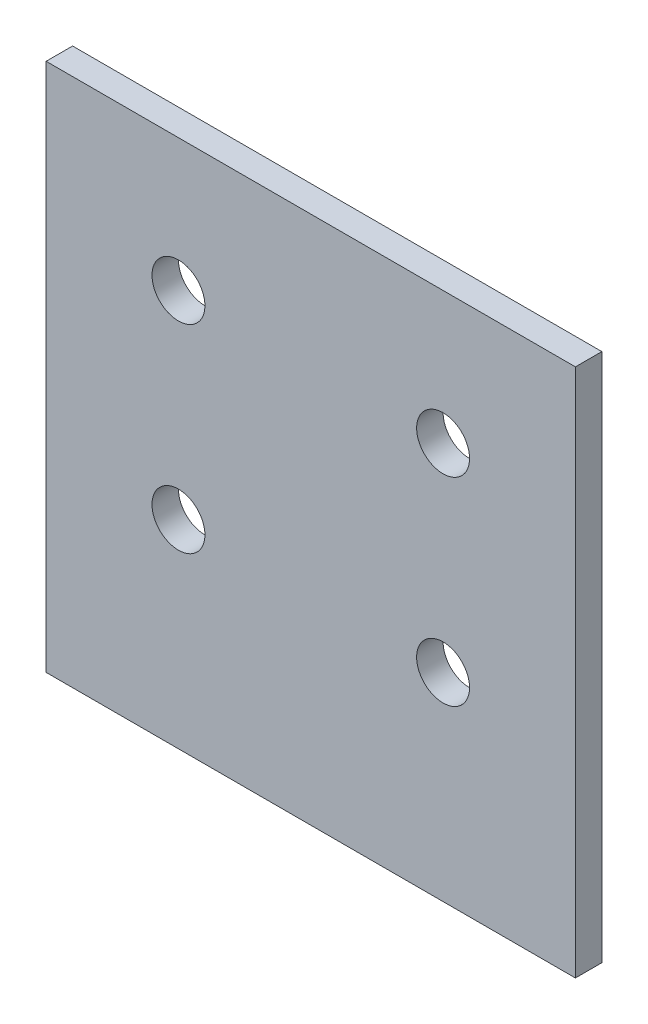
SolidWorks part; units mm, degrees
ref_plane "Front Plane" through (0, 0, 0) normal (0, 0, 1) x (1, 0, 0)
ref_plane "Top Plane" through (0, 0, 0) normal (0, 1, 0) x (1, 0, 0)
ref_plane "Right Plane" through (0, 0, 0) normal (1, 0, 0) x (0, 0, -1)
sketch "Sketch1" plane through (0, 0, 0) normal (0, 0, 1) x (1, 0, 0)
  line L0 (10, 40) -> (10, 0) construction
  line L1 (0, 0) -> (40, 0)
  line L2 (0, 0) -> (0, 40)
  line L3 (0, 40) -> (40, 40)
  line L4 (40, 0) -> (40, 40)
  line L5 (40, 9.4366) -> (30, 9.4366) construction
  line L6 (30, 40) -> (30, 0) construction
  line L7 (10, 30) -> (30, 30) construction
  line L8 (10, 15) -> (30, 15) construction
  circle A0 centre (10, 30) radius 2
  circle A1 centre (10, 15) radius 2
  circle A2 centre (30, 30) radius 2
  circle A3 centre (30, 15) radius 2
  dimension "D6" = 4
  dimension "D1" = 40
  dimension "D2" = 40
  dimension "D3" = 30
  dimension "D4" = 15
  dimension "D5" = 10
  dimension "D7" = 10
extrude "Boss-Extrude1" add sketch "Sketch1" along normal blind 2
